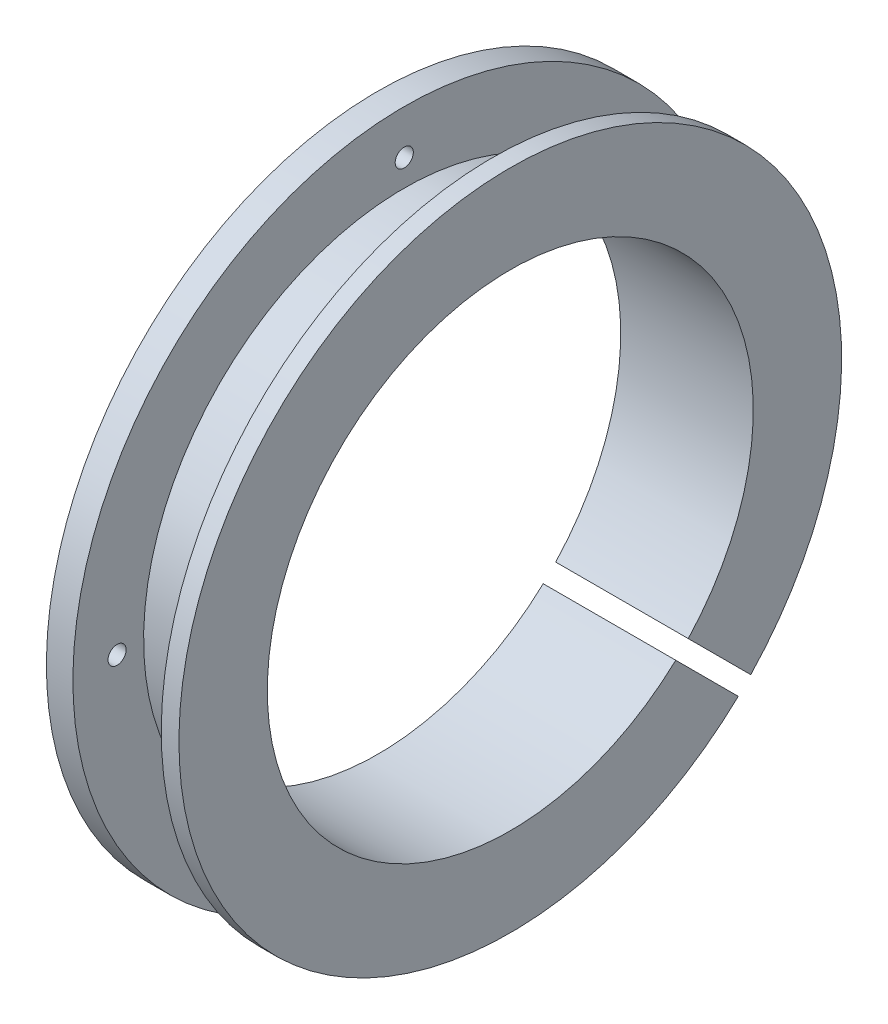
SolidWorks part; units mm, degrees
material "1060 Alloy"
ref_plane "Front Plane" through (0, 0, 0) normal (0, 0, 1) x (1, 0, 0)
ref_plane "Top Plane" through (0, 0, 0) normal (0, 1, 0) x (1, 0, 0)
ref_plane "Right Plane" through (0, 0, 0) normal (1, 0, 0) x (0, 0, -1)
sketch "Sketch1" plane through (0, 0, 0) normal (0, 0, 1) x (1, 0, 0)
  line L0 (0, 0) -> (-116.8977, 0) construction
  line L1 (-15, 27.5) -> (0, 27.5)
  line L2 (0, 27.5) -> (0, 37.5)
  line L3 (0, 37.5) -> (-2, 37.5)
  line L4 (-2, 37.5) -> (-2, 29.5)
  line L5 (-2, 29.5) -> (-12, 29.5)
  line L6 (-12, 29.5) -> (-12, 37.5)
  line L7 (-12, 37.5) -> (-15, 37.5)
  line L8 (-15, 37.5) -> (-15, 27.5)
  dimension "D1" = 37.5
  dimension "D2" = 2
  dimension "D3" = 3
  dimension "D4" = 10
  dimension "D5" = 10
  dimension "D6" = 2
revolve "Revolve1" add sketch "Sketch1" angle 360 about L0
hole_wizard "M2.5x0.45 Tapped Hole2" positions "Sketch5" profile "Sketch4" tap size "M2.5x0.45" standard "Ansi Metric"
sketch "Sketch5" plane through (-15, 0, 0) normal (-1, 0, 0) x (0, 0, 1)
  point P5 (0, -32.5)
  point P8 (-32.5, 0)
  point P14 (32.5, 0)
  point P17 (0, 32.5)
sketch "Sketch4" plane through (-15, -32.5, 0) normal (0, 1, 0) x (0, 0, 1)
  line L0 (0, 0) -> (0, 6.9659)
  line L1 (0, 6.9659) -> (1.025, 6.35)
  line L2 (1.025, 6.35) -> (1.025, 0)
  line L5 (1.025, 0) -> (0, 0)
  line L10 (0, 6.9659) -> (-1.025, 6.35) construction
  line L11 (0, -6.35) -> (0, 107.95) construction
  dimension "Tap Drill Dia." = 2.05
  dimension "Tap Drill Depth" = 6.35
  dimension "Drill Angle" = 118
cosmetic thread "Hole Thread5"
cosmetic thread "Hole Thread6"
cosmetic thread "Hole Thread7"
cosmetic thread "Hole Thread8"
sketch "Sketch6" plane through (0, 0, 0) normal (1, 0, 0) x (0, 0, -1)
  line L0 (0, -37.5) -> (0, 0) construction
  line L1 (0, 0) -> (37.5, 0) construction
  line L2 (37.5, 0) -> (0, -37.5) construction
  line L3 (18.75, -18.75) -> (0, 0) construction
  line L4 (18.75, -18.75) -> (26.5165, -26.5165) construction
  line L5 (27.2236, -25.8094) -> (25.8094, -27.2236)
  line L6 (25.8094, -27.2236) -> (18.7255, -20.1397)
  line L7 (18.7255, -20.1397) -> (20.1397, -18.7255)
  line L8 (20.1397, -18.7255) -> (27.2236, -25.8094)
  circle A0 centre (0, 0) radius 37.5 construction
  circle A1 centre (0, 0) radius 27.5 construction
  dimension "D1" = 1
  dimension "D2" = 1
extrude "Cut-Extrude1" cut sketch "Sketch6" against normal through all
